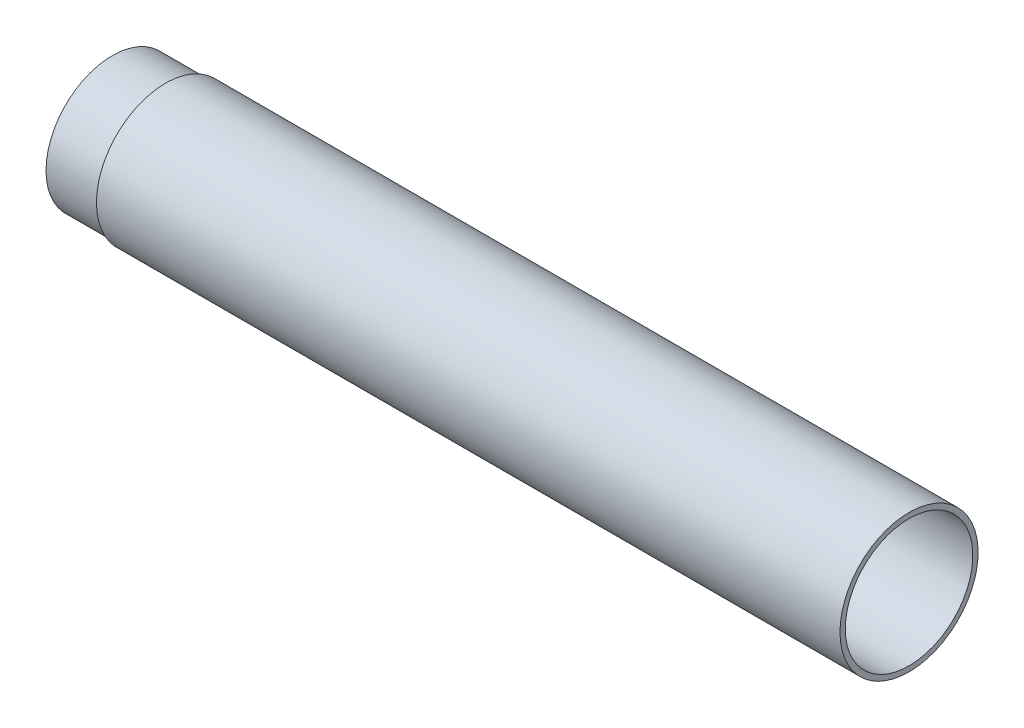
SolidWorks part; units mm, degrees
material "Copper"
ref_plane "Front Plane" through (0, 0, 0) normal (0, 0, 1) x (1, 0, 0)
ref_plane "Top Plane" through (0, 0, 0) normal (0, 1, 0) x (1, 0, 0)
ref_plane "Right Plane" through (0, 0, 0) normal (1, 0, 0) x (0, 0, -1)
sketch "Sketch1" plane through (0, 0, 0) normal (0, 0, 1) x (1, 0, 0)
  line L0 (0, 0) -> (22.4873, 0)
  line L5 (15.2485, 16.5166) -> (193.0485, 16.5166)
  line L6 (2.5485, 15.2466) -> (193.0485, 15.2466)
  line L7 (193.0485, 16.5166) -> (193.0485, 15.2466)
  line L11 (15.2485, 16.5166) -> (15.2485, 15.8816)
  line L12 (15.2485, 15.8816) -> (2.5485, 15.8816)
  line L13 (2.5485, 15.8816) -> (2.5485, 15.2466)
  dimension "D1" = 15.2466
  dimension "D2" = 177.8
  dimension "D3" = 12.7
  dimension "D4" = 1.27
revolve "Revolve1" add sketch "Sketch1" angle 360 about L0
ref_plane "Plane1" through (0, 16.5166, 0) normal (0, 1, 0) x (1, 0, 0)
sketch "Sketch2" plane through (0, 16.5166, 0) normal (0, 1, 0) x (1, 0, 0)
  line L0 (25.4, 0) -> (25.4, 2.54)
  line L1 (15.2485, 0) -> (193.0485, 0) construction
  line L2 (25.4, 0) -> (25.4, -2.54)
  line L3 (25.4, 2.54) -> (25.4, -2.54) construction
  line L4 (26.9875, 2.54) -> (26.9875, -2.54)
  line L5 (23.8125, 2.54) -> (23.8125, -2.54)
  arc A1 (26.9875, 2.54) -> (23.8125, 2.54) centre (25.4, 2.54) ccw
  arc A2 (23.8125, -2.54) -> (26.9875, -2.54) centre (25.4, -2.54) ccw
  point P4 (25.4, 0)
extrude "Cut-Extrude1" [suppressed] cut sketch "Sketch2" against normal blind 7.62 contours L4 A2 L5 A1
pattern_circular "CirPattern1" [suppressed] count 3 every 120
